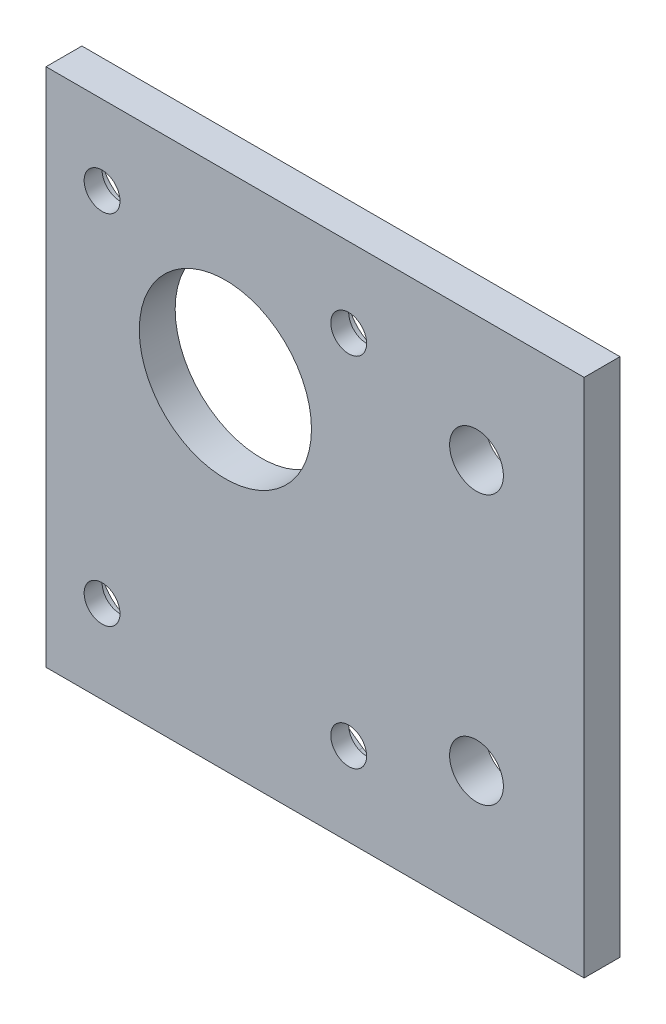
SolidWorks part; units mm, degrees
ref_plane "Front Plane" through (0, 0, 0) normal (0, 0, 1) x (1, 0, 0)
ref_plane "Top Plane" through (0, 0, 0) normal (0, 1, 0) x (1, 0, 0)
ref_plane "Right Plane" through (0, 0, 0) normal (1, 0, 0) x (0, 0, -1)
sketch "Sketch1" plane through (0, 0, 0) normal (0, 0, 1) x (1, 0, 0)
  line L0 (13.75, -19.7) -> (9.6769, -16.8) construction
  line L3 (20, 29) -> (40, 29)
  line L8 (20, -29) -> (-20, -29)
  line L9 (20, -29) -> (20, 29) construction
  line L10 (40, 29) -> (40, -29)
  line L11 (20, 29) -> (-20, 29)
  line L14 (-20, -29) -> (-20, 29)
  line L15 (20, -29) -> (-20, 29) construction
  line L16 (20, 29) -> (-20, -29) construction
  line L17 (11.314, -23.1214) -> (7.2409, -20.2214)
  line L18 (16.186, -16.2786) -> (12.1129, -13.3786)
  line L19 (0, -29) -> (0, 29) construction
  line L22 (40, -29) -> (20, -29)
  circle A18 centre (-13.75, 20.15) radius 4.2
  circle A19 centre (13.75, 20.15) radius 4.2
  circle A20 centre (-13.75, -19.7) radius 4.2
  arc A21 (11.314, -23.1214) -> (16.186, -16.2786) centre (13.75, -19.7) ccw
  arc A22 (12.1129, -13.3786) -> (7.2409, -20.2214) centre (9.6769, -16.8) ccw
  circle A23 centre (0, 8.8) radius 9.6
  circle A24 centre (-5.725, -6.1) radius 4.2
  circle A25 centre (5.725, -6.1) radius 4.2
  point P0 (0, 0)
  point P14 (6.2555, -14.364)
  point P18 (0, 0)
  point P19 (0, 0)
  point P20 (0, 0)
  point P31 (11.7135, -18.25)
  point P37 (5.725, -10.3)
  point P43 (20, 29)
  point P46 (-20, 29)
  dimension "D1" = 58
  dimension "D2" = 40
  dimension "D4" = 8.4
  dimension "D5" = 8.4
  dimension "D6" = 19.2
  dimension "D7" = 9.3
  dimension "D8" = 27.5
  dimension "D9" = 12.2
  dimension "D10" = 5
  dimension "D11" = 39.85
  dimension "D12" = 20.2
  dimension "D13" = 11.45
  dimension "D14" = 22.9
  dimension "D15" = 20
extrude "Boss-Extrude1" add sketch "Sketch1" along normal blind 2
sketch "Sketch4" plane through (0, 0, 2) normal (0, 0, 1) x (1, 0, 0)
  line L1 (-20, 29) -> (40, 29)
  line L2 (-20, 29) -> (-20, -29)
  line L5 (-20, -29) -> (-20, 29) construction
  line L7 (40, 29) -> (-20, 29) construction
  line L8 (-20, -29) -> (40, -29)
  line L11 (40, -29) -> (40, 29)
  circle A2 centre (-13.75, -19.7) radius 2
  circle A3 centre (-13.75, 20.15) radius 2
  circle A4 centre (13.75, 20.15) radius 2
  circle A10 centre (13.75, -19.7) radius 2
  circle A11 centre (0, 8.8) radius 9.6
  circle A12 centre (0, 8.8) radius 9.6 construction
  dimension "D1" = 4
extrude "Boss-Extrude3" add sketch "Sketch4" along normal blind 2
sketch "Sketch5" plane through (0, 0, 4) normal (0, 0, 1) x (1, 0, 0)
  line L0 (-20, 0) -> (40, 0) construction
  line L1 (-20, 29) -> (-20, -29) construction
  line L2 (40, -29) -> (40, 29) construction
  circle A0 centre (28, 15) radius 3
  circle A1 centre (28, -15) radius 3
  point P3 (0, 0)
  point P7 (0, 0)
  point P9 (29.228, 18.1286)
  point P10 (28.8476, 15)
  point P17 (0, 0)
  point P18 (0, 0)
  dimension "D1" = 6
  dimension "D2" = 15
  dimension "D3" = 12
extrude "Cut-Extrude1" cut sketch "Sketch5" against normal up to surface (4 mm away) up to face at (9.925, -6.1, 0)
